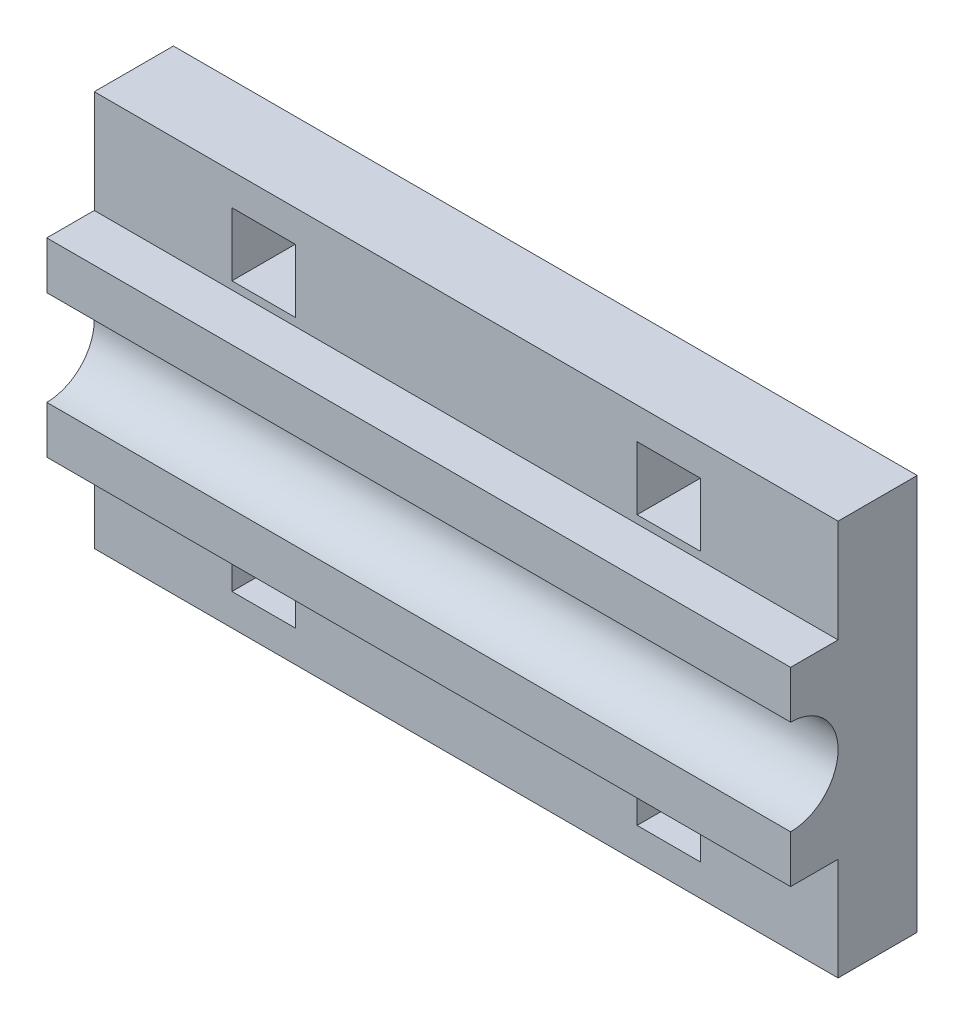
SolidWorks part; units mm, degrees
ref_plane "Plan de face" through (0, 0, 0) normal (0, 0, 1) x (1, 0, 0)
ref_plane "Plan de dessus" through (0, 0, 0) normal (0, 1, 0) x (1, 0, 0)
ref_plane "Plan de droite" through (0, 0, 0) normal (1, 0, 0) x (0, 0, -1)
sketch "Esquisse1" plane through (0, 0, 0) normal (0, 0, 1) x (1, 0, 0)
  line L0 (-36, 5) -> (-36, -20)
  line L1 (-36, -20) -> (11, -20)
  line L2 (11, -20) -> (11, 5)
  line L3 (11, 5) -> (-36, 5)
  point P2 (-12.5, 5)
  dimension "D1" = 47
  dimension "D2" = 5
  dimension "D3" = 25
  dimension "D4" = 11
extrude "Boss.-Extru.1" add sketch "Esquisse1" along normal blind 5
sketch "Esquisse2" plane through (0, 0, 5) normal (0, 0, 1) x (1, 0, 0)
  line L0 (-36, 5) -> (-36, -20) construction
  line L1 (-27.3, -18) -> (-23.3, -18)
  line L2 (-27.3, -18) -> (-27.3, -14)
  line L3 (-27.3, -14) -> (-23.3, -14)
  line L4 (-23.3, -18) -> (-23.3, -14)
  line L5 (6.1175, -7.5) -> (-8.0239, -7.5) construction
  line L7 (-27.3, 3) -> (-23.3, 3)
  line L8 (-23.3, 3) -> (-23.3, -1)
  line L9 (-27.3, -1) -> (-23.3, -1)
  line L10 (-27.3, 3) -> (-27.3, -1)
  line L11 (-12.5, -16.8218) -> (-12.5, 13.6319) construction
  line L12 (2.3, 3) -> (-1.7, 3)
  line L13 (2.3, 3) -> (2.3, -1)
  line L14 (2.3, -1) -> (-1.7, -1)
  line L15 (-1.7, 3) -> (-1.7, -1)
  line L16 (-1.7, -18) -> (-1.7, -14)
  line L17 (-36, -20) -> (11, -20) construction
  line L18 (2.3, -14) -> (-1.7, -14)
  line L19 (2.3, -18) -> (2.3, -14)
  line L20 (2.3, -18) -> (-1.7, -18)
  line L21 (11, 5) -> (-36, 5) construction
  point P26 (-12.5, 5)
  dimension "D1" = 8.7
  dimension "D2" = 2
  dimension "D3" = 4
  dimension "D4" = 4
extrude "Enlèv. mat.-Extru.1" cut sketch "Esquisse2" against normal blind 5
sketch "Esquisse4" plane through (0, 0, 5) normal (0, 0, 1) x (1, 0, 0)
  line L0 (-36, 5) -> (-36, -20) construction
  line L1 (-36, -13.5) -> (11, -13.5)
  line L2 (-36, -13.5) -> (-36, -1.5)
  line L3 (-36, -1.5) -> (11, -1.5)
  line L4 (11, -13.5) -> (11, -1.5)
  line L5 (11, -20) -> (11, 5) construction
  line L6 (11, 5) -> (-36, 5) construction
  dimension "D1" = 12
  dimension "D2" = 6.5
extrude "Boss.-Extru.2" add sketch "Esquisse4" along normal blind 3
sketch "Esquisse5" plane through (11, 0, 0) normal (1, 0, 0) x (0, 0, -1)
  line L0 (-8, -7.5) -> (4.5084, -7.5) construction
  line L1 (-8, -13.5) -> (-8, -1.5) construction
  circle A0 centre (-8, -7.5) radius 3
  point P6 (0, 0)
  dimension "D1" = 6
extrude "Enlèv. mat.-Extru.2" cut sketch "Esquisse5" against normal blind 63
